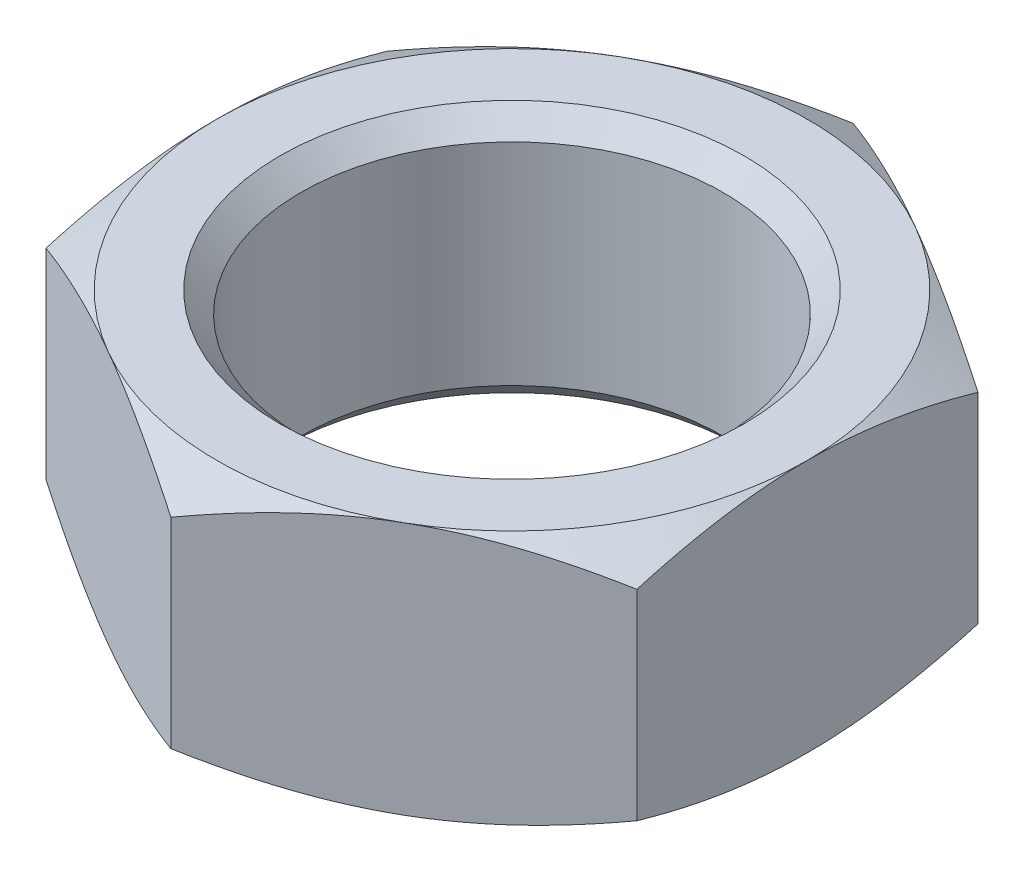
SolidWorks part; units mm, degrees
ref_plane "Front Plane" through (0, 0, 0) normal (0, 0, 1) x (1, 0, 0)
ref_plane "Top Plane" through (0, 0, 0) normal (0, 1, 0) x (1, 0, 0)
ref_plane "Right Plane" through (0, 0, 0) normal (1, 0, 0) x (0, 0, -1)
sketch "Sketch1" plane through (0, 0, 0) normal (0, 1, 0) x (1, 0, 0)
  line L1 (14, -8.0829) -> (14, 8.0829)
  line L2 (14, 8.0829) -> (0, 16.1658)
  line L3 (0, 16.1658) -> (-14, 8.0829)
  line L4 (-14, 8.0829) -> (-14, -8.0829)
  line L5 (-14, -8.0829) -> (0, -16.1658)
  line L6 (0, -16.1658) -> (14, -8.0829)
  circle A0 centre (0, 0) radius 14 construction
  dimension "D1" = 28
extrude "Boss-Extrude1" add sketch "Sketch1" along normal mid plane 12
sketch "Sketch2" plane through (0, 6, 0) normal (0, 1, 0) x (1, 0, 0)
  line L0 (14, 8.0829) -> (0, 16.1658) construction
  circle A0 centre (0, 0) radius 14
extrude "Cut-Extrude1" cut sketch "Sketch2" against normal blind 12 draft 60 flip side to cut
mirror "Mirror1" about plane through (0, 0, 0) normal (0, 1, 0) of "Cut-Extrude1"
sketch "Sketch3" plane through (0, 6, 0) normal (0, 1, 0) x (1, 0, 0)
  circle A0 centre (0, 0) radius 10
  dimension "D1" = 20
extrude "Cut-Extrude2" cut sketch "Sketch3" against normal through all
chamfer "Chamfer1" distance 1 angle 45 2 edges at (0, -6, 10) (0, 6, 10)
